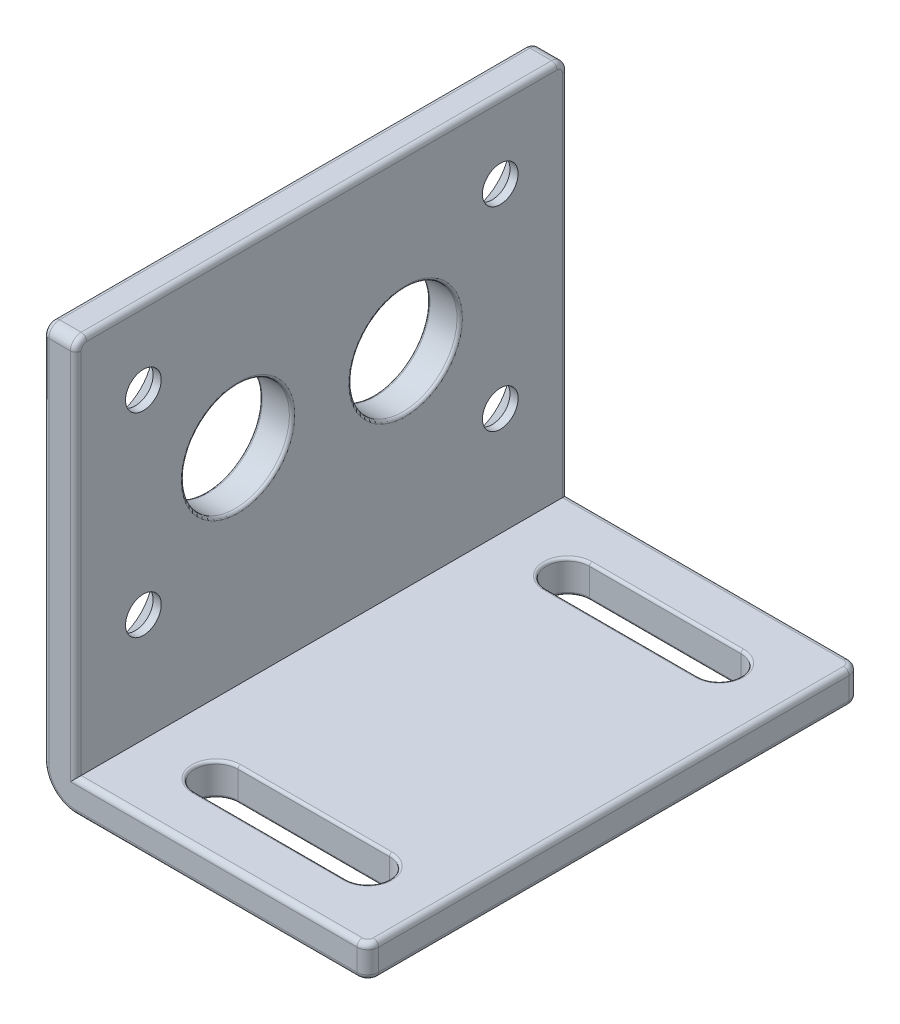
SolidWorks part; units mm, degrees
ref_plane "前视基准面" through (0, 0, 0) normal (0, 0, 1) x (1, 0, 0)
ref_plane "上视基准面" through (0, 0, 0) normal (0, 1, 0) x (1, 0, 0)
ref_plane "右视基准面" through (0, 0, 0) normal (1, 0, 0) x (0, 0, -1)
other "Configuration Table"
sketch "草图2" plane through (0, 0, 0) normal (0, 0, 1) x (1, 0, 0)
  line L0 (0, 0) -> (0, 38)
  line L1 (0, 38) -> (3, 38)
  line L2 (3, 38) -> (3, 3)
  line L3 (3, 3) -> (30, 3)
  line L4 (30, 3) -> (30, 0)
  line L5 (30, 0) -> (0, 0)
  dimension "D1" = 38
  dimension "D2" = 3
  dimension "D3" = 30
  dimension "D4" = 3
extrude "凸台-拉伸1" add sketch "草图2" against normal blind 45.5
sketch "草图3" plane through (0, 0, 0) normal (-1, 0, 0) x (0, 0, 1)
  line L0 (-22.75, 38) -> (-22.75, 0) construction
  line L1 (-30.5, 22) -> (-15, 22) construction
  line L2 (-39.25, 13) -> (-6.25, 13) construction
  line L3 (-39.25, 13) -> (-39.25, 31) construction
  line L4 (-39.25, 31) -> (-6.25, 31) construction
  line L5 (-6.25, 13) -> (-6.25, 31) construction
  line L6 (-39.25, 13) -> (-6.25, 31) construction
  line L7 (-39.25, 31) -> (-6.25, 13) construction
  line L8 (0, 0) -> (0, 38)
  line L9 (0, 38) -> (-45.5, 38)
  line L10 (-45.5, 38) -> (-45.5, 0)
  line L11 (-45.5, 0) -> (0, 0)
  line L12 (0, 0) -> (0, 38)
  line L13 (0, 38) -> (-45.5, 38)
  line L14 (-45.5, 38) -> (-45.5, 0)
  line L15 (-45.5, 0) -> (0, 0)
  circle A0 centre (-6.25, 31) radius 1.65
  circle A1 centre (-6.25, 13) radius 1.65
  circle A2 centre (-39.25, 13) radius 1.65
  circle A3 centre (-39.25, 31) radius 1.65
  circle A4 centre (-15, 22) radius 5
  circle A5 centre (-30.5, 22) radius 5
  point P5 (-22.75, 22)
  point P14 (-22.75, 22)
  dimension "D6" = 3.3
  dimension "D7" = 10
  dimension "D2" = 18
  dimension "D3" = 33
  dimension "D4" = 15
  dimension "D5" = 16
  dimension "D1" = 0
extrude "切除-拉伸1" cut sketch "草图3" against normal through all contours A3 | A5 | A2 | A4 | A1 | A0
chamfer "倒角2" distance 2.25 angle 45 4 edges at (0, 31, -4.6) (0, 13, -4.6) (0, 13, -37.6) (0, 31, -37.6)
sketch "草图4" plane through (0, 0, 0) normal (0, -1, 0) x (1, 0, 0)
  line L0 (0, -22.75) -> (30, -22.75) construction
  line L1 (16.5, 2.5) -> (16.5, -45.5) construction
  line L2 (9.5, -6.5) -> (23.5, -6.5) construction
  line L3 (9.5, -39) -> (23.5, -39) construction
  line L4 (30, 0) -> (0, 0)
  line L5 (0, 0) -> (0, -45.5)
  line L6 (0, -45.5) -> (30, -45.5)
  line L7 (30, -45.5) -> (30, 0)
  line L8 (30, 0) -> (0, 0)
  line L9 (0, 0) -> (0, -45.5)
  line L10 (0, -45.5) -> (30, -45.5)
  line L11 (30, -45.5) -> (30, 0)
  line L12 (9.5, -4.5) -> (23.5, -4.5)
  line L13 (9.5, -8.5) -> (23.5, -8.5)
  line L14 (9.5, -41) -> (23.5, -41)
  line L15 (9.5, -37) -> (23.5, -37)
  line L16 (0, -45.5) -> (30, -45.5) construction
  arc A0 (9.5, -4.5) -> (9.5, -8.5) centre (9.5, -6.5) ccw
  arc A1 (23.5, -8.5) -> (23.5, -4.5) centre (23.5, -6.5) ccw
  arc A2 (9.5, -41) -> (9.5, -37) centre (9.5, -39) cw
  arc A3 (23.5, -37) -> (23.5, -41) centre (23.5, -39) cw
  point P12 (16.5, -6.5)
  point P17 (16.5, -39)
  point P22 (16.5, -45.5)
  dimension "D2" = 28.5
  dimension "D3" = 4
  dimension "D4" = 14
  dimension "D5" = 6.5
  dimension "D6" = 4.5
  dimension "D7" = 6.5
  dimension "D1" = 0
extrude "切除-拉伸2" cut sketch "草图4" against normal through all contours A3 L15 A2 L14 | L13 A1 L12 A0
fillet "圆角1" radius 1 4 edges at (30, 1.5, -45.5) (30, 1.5, 0) (1.5, 38, -45.5) (1.5, 38, 0)
fillet "圆角2" radius 3 1 edges at (0, 0, -22.75)
fillet "圆角3" radius 0.5 22 edges at (3, 20, -45.5) (3, 37.7071, -45.2071) (3, 38, -22.75) (3, 37.7071, -0.2929) (16, 3, -45.5) (29.7071, 3, -45.2071) (30, 3, -22.75) (29.7071, 3, -0.2929) (0, 37.7071, -0.2929) (0, 38, -22.75) (0, 37.7071, -45.2071) (0, 20, -45.5) (0.8787, 0.8787, -45.5) (16, 0, -45.5) (29.7071, 0, -45.2071) (30, 0, -22.75) (29.7071, 0, -0.2929) (3, 20, 0) (16, 3, 0) (16, 0, 0) (0.8787, 0.8787, 0) (0, 20, 0)
fillet "圆角4" radius 0.25 20 edges at (7.5, 0, -6.5) (16.5, 0, -4.5) (25.5, 0, -6.5) (25.5, 3, -6.5) (16.5, 3, -4.5) (7.5, 3, -6.5) (16.5, 3, -37) (25.5, 3, -39) (25.5, 0, -39) (16.5, 0, -37) (16.5, 0, -8.5) (16.5, 3, -8.5) (16.5, 0, -41) (16.5, 3, -41) (7.5, 3, -39) (7.5, 0, -39) (0, 22, -25.5) (3, 27, -30.5) (0, 22, -10) (3, 27, -15)
